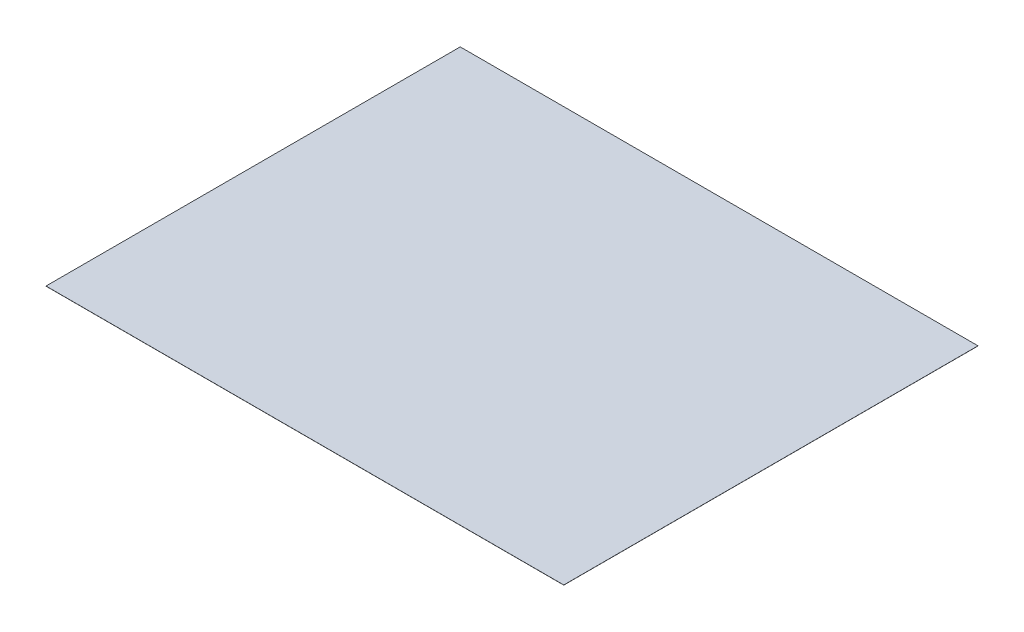
SolidWorks part; units mm, degrees
material "PE High Density Film"
ref_plane "Front Plane" through (0, 0, 0) normal (0, 0, 1) x (1, 0, 0)
ref_plane "Top Plane" through (0, 0, 0) normal (0, 1, 0) x (1, 0, 0)
ref_plane "Right Plane" through (0, 0, 0) normal (1, 0, 0) x (0, 0, -1)
sketch "Sketch1" plane through (0, 0, 0) normal (0, 1, 0) x (1, 0, 0)
  line L1 (-3048, -2438.4) -> (3048, -2438.4)
  line L2 (-3048, -2438.4) -> (-3048, 2438.4)
  line L3 (-3048, 2438.4) -> (3048, 2438.4)
  line L4 (3048, -2438.4) -> (3048, 2438.4)
  line L5 (-3048, -2438.4) -> (3048, 2438.4) construction
  line L6 (-3048, 2438.4) -> (3048, -2438.4) construction
  point P0 (0, 0)
  dimension "D1" = 4876.8
  dimension "D2" = 6096
extrude "Boss-Extrude1" add sketch "Sketch1" along normal blind 1.5875
